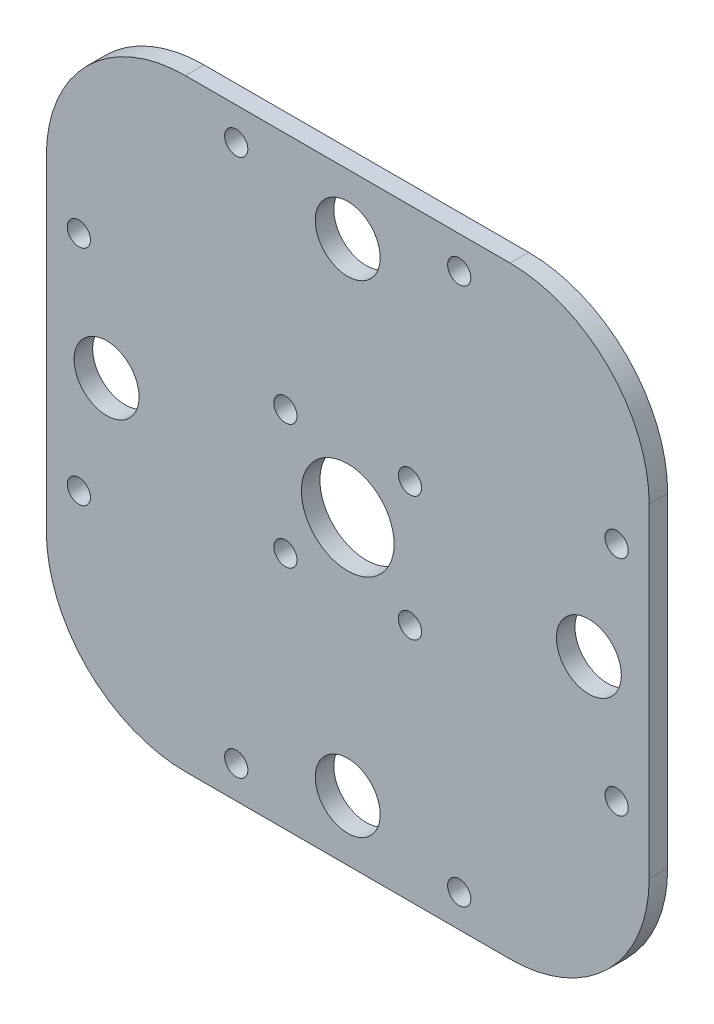
SolidWorks part; units mm, degrees
material "Thornel Mat VMA"
ref_plane "Alzado" through (0, 0, 0) normal (0, 0, 1) x (1, 0, 0)
ref_plane "Planta" through (0, 0, 0) normal (0, 1, 0) x (1, 0, 0)
ref_plane "Vista lateral" through (0, 0, 0) normal (1, 0, 0) x (0, 0, -1)
sketch "Croquis1" plane through (0, 0, 0) normal (0, 0, 1) x (1, 0, 0)
  line L0 (17.5, 0) -> (32.5, 0) construction
  line L1 (-32.5, -32.5) -> (32.5, -32.5)
  line L2 (-32.5, -32.5) -> (-32.5, 32.5)
  line L3 (-32.5, 32.5) -> (32.5, 32.5)
  line L4 (32.5, -32.5) -> (32.5, 32.5)
  line L5 (-32.5, -32.5) -> (32.5, 32.5) construction
  line L6 (-32.5, 32.5) -> (32.5, -32.5) construction
  line L7 (0, 17.5) -> (0, 32.5) construction
  circle A0 centre (0, 0) radius 17.5 construction
  circle A5 centre (-27.5503, 27.5503) radius 3 construction
  circle A6 centre (27.5503, 27.5503) radius 3 construction
  circle A7 centre (27.5503, -27.5503) radius 3 construction
  circle A8 centre (-27.5503, -27.5503) radius 3 construction
  circle A9 centre (0, 0) radius 5
  circle A10 centre (0, 0) radius 9.5 construction
  circle A11 centre (-6.7175, 6.7175) radius 1.25
  circle A12 centre (6.7175, 6.7175) radius 1.25
  circle A13 centre (6.7175, -6.7175) radius 1.25
  circle A14 centre (-6.7175, -6.7175) radius 1.25
  point P0 (0, 0)
  point P21 (0, 0)
  point P32 (0, 0)
  point P35 (0, 0)
  dimension "D1" = 35
  dimension "D2" = 19
  dimension "D6" = 6
  dimension "D9" = 65
  dimension "D3" = 2.5
  dimension "D10" = 10
  dimension "D5" = 15
  dimension "D8" = 7
  dimension "D7" = 4
  dimension "D4" = 4
extrude "Saliente-Extruir1" add sketch "Croquis1" along normal blind 2
fillet "Redondeo1" radius 15 4 edges at (32.5, 32.5, 1) (32.5, -32.5, 1) (-32.5, -32.5, 1) (-32.5, 32.5, 1)
sketch "Croquis2" plane through (0, 0, 2) normal (0, 0, 1) x (1, 0, 0)
  circle A9 centre (-26, 0) radius 3.5
  circle A12 centre (0, 26) radius 3.5
  circle A13 centre (26, 0) radius 3.5
  circle A14 centre (0, -26) radius 3.5
  circle A15 centre (0, 0) radius 20 construction
  point P27 (0, 0)
  point P36 (0, 0)
  dimension "D3" = 7
  dimension "D6" = 40
  dimension "D4" = 26
  dimension "D5" = 4
sketch "Croquis3" plane through (0, 0, 2) normal (0, 0, 1) x (1, 0, 0)
  line L0 (0, 0) -> (-27.5503, 27.5503) construction
  line L1 (0, 0) -> (-26, 0) construction
  line L2 (-19.0919, 19.0919) -> (-9.1924, 28.9914) construction
  line L4 (-9.1924, 28.9914) -> (-12.0208, 31.8198) construction
  line L5 (-12.0208, 31.8198) -> (-31.8198, 12.0208) construction
  line L6 (-31.8198, 12.0208) -> (-28.9914, 9.1924) construction
  line L7 (-28.9914, 9.1924) -> (-19.0919, 19.0919) construction
  line L8 (-19.0919, 19.0919) -> (-14.1421, 14.1421) construction
  circle A0 centre (0, 0) radius 20 construction
  circle A1 centre (-28.9914, 12.0208) radius 1.25
  circle A2 centre (-12.0208, 28.9914) radius 1.25
  circle A3 centre (12.0208, 28.9914) radius 1.25
  circle A4 centre (28.9914, 12.0208) radius 1.25
  circle A5 centre (28.9914, -12.0208) radius 1.25
  circle A6 centre (12.0208, -28.9914) radius 1.25
  circle A7 centre (-12.0208, -28.9914) radius 1.25
  circle A8 centre (-28.9914, -12.0208) radius 1.25
  point P31 (0, 0)
  dimension "D1" = 40
  dimension "D5" = 2
  dimension "D7" = 27
  dimension "D8" = 2.5
  dimension "D2" = 4
  dimension "D3" = 14
  dimension "D4" = 28
  dimension "D6" = 2
  dimension "D9" = 4
extrude "Cortar-Extruir1" cut sketch "Croquis2" against normal up to vertex (2 mm away)
extrude "Cortar-Extruir2" cut sketch "Croquis3" against normal up to vertex (2 mm away)
